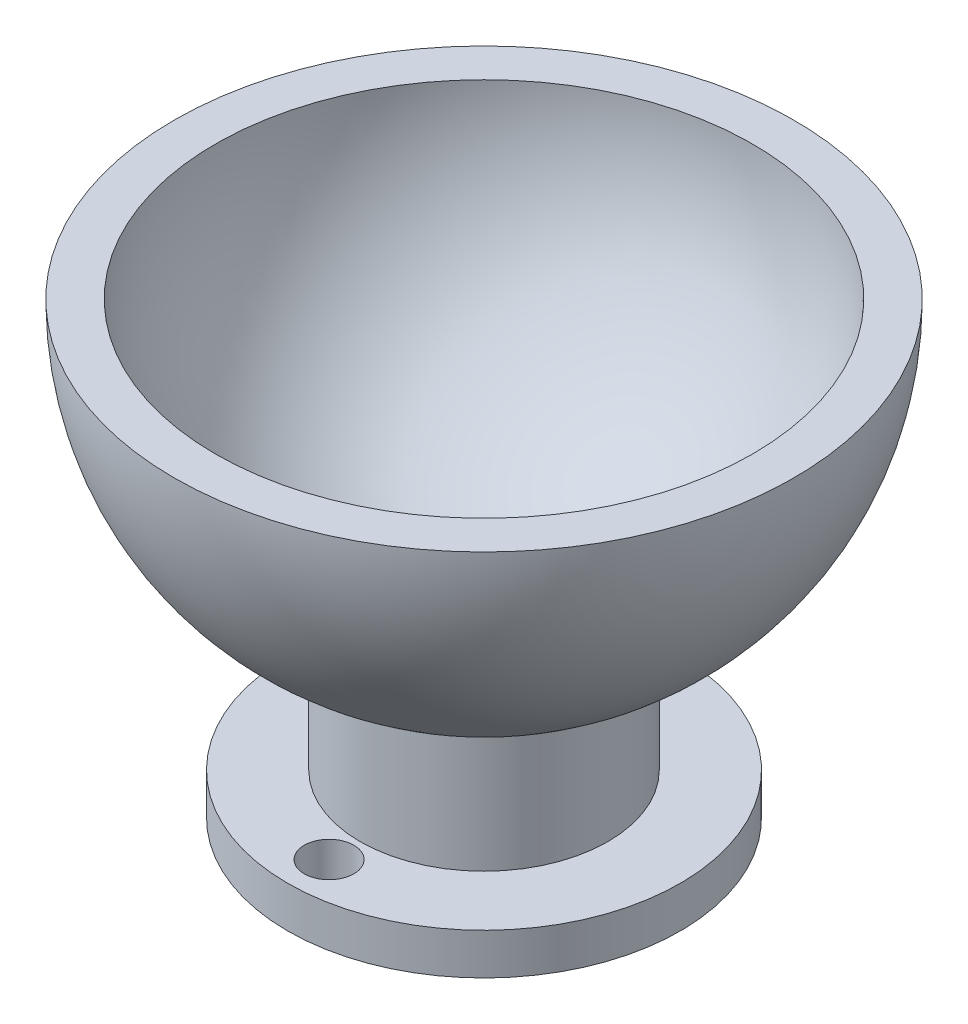
SolidWorks part; units mm, degrees
ref_plane "Front Plane" through (0, 0, 0) normal (0, 0, 1) x (1, 0, 0)
ref_plane "Top Plane" through (0, 0, 0) normal (0, 1, 0) x (1, 0, 0)
ref_plane "Right Plane" through (0, 0, 0) normal (1, 0, 0) x (0, 0, -1)
sketch "Sketch2" plane through (0, 0, 0) normal (0, 1, 0) x (1, 0, 0)
  circle A0 centre (0, 0) radius 12.065
  dimension "D1" = 24.13
extrude "Boss-Extrude1" add sketch "Sketch2" along normal blind 2.54
sketch "Sketch3" plane through (0, 2.54, 0) normal (0, 1, 0) x (1, 0, 0)
  circle A0 centre (0, 0) radius 7.62
  dimension "D1" = 15.24
extrude "Boss-Extrude2" add sketch "Sketch3" along normal blind 7.62
sketch "Sketch5" plane through (0, 0, 0) normal (0, 0, 1) x (1, 0, 0)
  line L1 (0, 47.8751) -> (0, 7.0617) construction
  line L4 (16.51, 27.6196) -> (19.05, 27.6196)
  line L5 (0, 8.5696) -> (0, 11.1096)
  arc A2 (0, 8.5696) -> (19.05, 27.6196) centre (0, 27.6196) ccw
  arc A3 (0, 11.1096) -> (16.51, 27.6196) centre (0, 27.6196) ccw
  dimension "D2" = 2.54
  dimension "D1" = 38.1
revolve "Revolve1" add sketch "Sketch5" angle 360 about L1
sketch "Sketch6" plane through (0, 0, 0) normal (0, -1, 0) x (1, 0, 0)
  line L0 (0, 12.065) -> (0, 6.985) construction
  circle A0 centre (0, 0) radius 12.065 construction
  circle A1 centre (0, 9.525) radius 1.524
  dimension "D2" = 3.048
  dimension "D1" = 5.08
extrude "Cut-Extrude1" cut sketch "Sketch6" against normal blind 5.08
